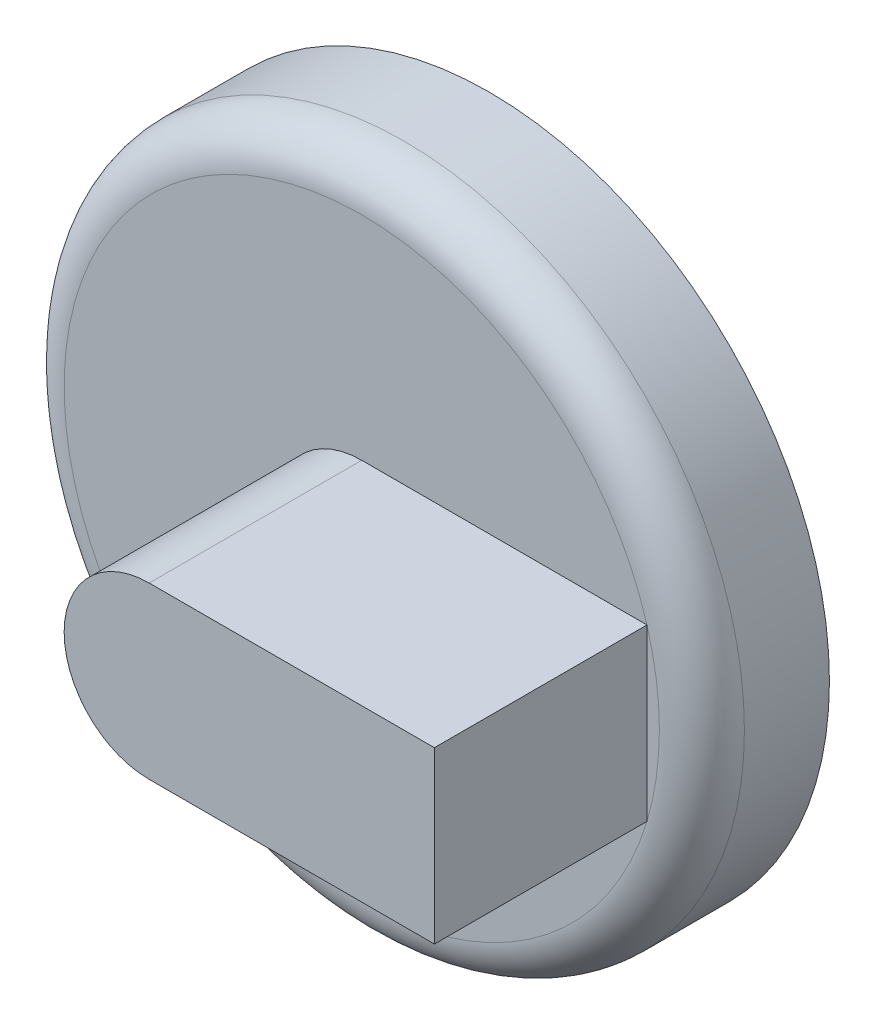
SolidWorks part; units mm, degrees
material "Silicon Dioxide"
ref_plane "Front Plane" through (0, 0, 0) normal (0, 0, 1) x (1, 0, 0)
ref_plane "Top Plane" through (0, 0, 0) normal (0, 1, 0) x (1, 0, 0)
ref_plane "Right Plane" through (0, 0, 0) normal (1, 0, 0) x (0, 0, -1)
sketch "Sketch1" plane through (0, 0, 0) normal (0, 0, 1) x (1, 0, 0)
  circle A0 centre (0, 0) radius 40
extrude "Boss-Extrude1" add sketch "Sketch1" along normal blind 15
fillet "Fillet1" radius 5 1 edges at (40, 0, 15)
sketch "Sketch2" plane through (0, 0, 15) normal (0, 0, 1) x (1, 0, 0)
  circle A0 centre (0, 0) radius 10
extrude "Boss-Extrude2" add sketch "Sketch2" along normal blind 25
scale "Scale1" scale about centroid uniform scaling yes scale factor 2
sketch "Sketch3" plane through (0, 0, 70.6849) normal (0, 0, 1) x (1, 0, 0)
  line L1 (0, 20) -> (67.082, 20)
  line L2 (0, 20) -> (0, -20)
  line L3 (0, -20) -> (67.082, -20)
  line L4 (67.082, 20) -> (67.082, -20)
  circle A0 centre (0, 0) radius 20 construction
  circle A1 centre (0, 0) radius 20 construction
  circle A2 centre (0, 0) radius 70 construction
extrude "Boss-Extrude3" add sketch "Sketch3" against normal blind 50
